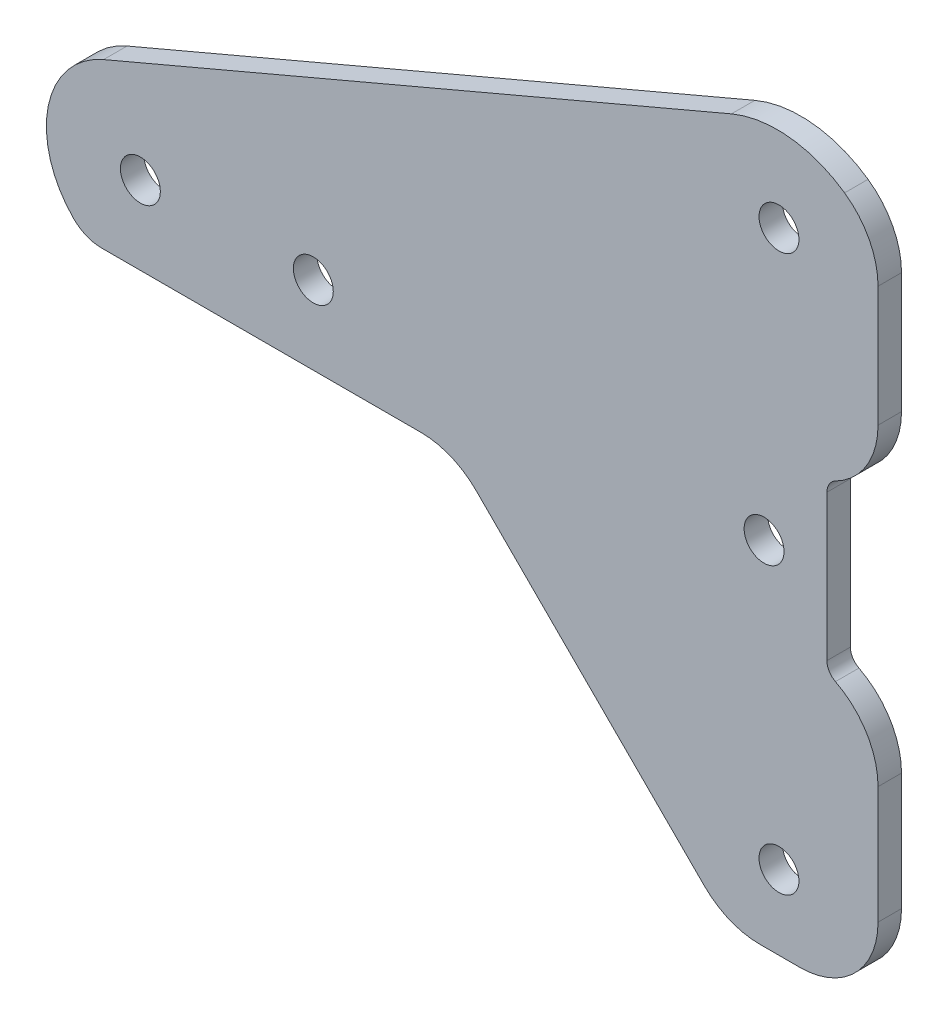
SolidWorks part; units mm, degrees
material "AISI 1020"
ref_plane "Front Plane" through (0, 0, 0) normal (0, 0, 1) x (1, 0, 0)
ref_plane "Top Plane" through (0, 0, 0) normal (0, 1, 0) x (1, 0, 0)
ref_plane "Right Plane" through (0, 0, 0) normal (1, 0, 0) x (0, 0, -1)
sketch "Sketch1" plane through (0, 0, 0) normal (0, 0, 1) x (1, 0, 0)
  line L0 (0, 20.0008) -> (0, 35.3808)
  line L1 (0, -20.0008) -> (0, -35.0008)
  line L2 (-18.7332, 45.0875) -> (-98.965, 10.9816)
  line L3 (-99.252, -10.003) -> (-58.412, -10.003)
  line L4 (-51.3409, -12.932) -> (-22.2011, -42.0718)
  line L5 (-15.13, -45.0008) -> (-10, -45.0008)
  line L6 (-6.53, 9.32) -> (-6.53, -9.32)
  arc A0 (0, -35.0008) -> (-10, -45.0008) centre (-10, -35.0008) cw
  arc A1 (-15.13, -45.0008) -> (-22.2011, -42.0718) centre (-15.13, -35.0008) cw
  arc A2 (0, 20.0008) -> (-5.4417, 11.1001) centre (-10, 20.0008) cw
  arc A3 (-5.4417, 11.1001) -> (-6.53, 9.32) centre (-4.53, 9.32) ccw
  arc A4 (0, -20.0008) -> (-5.4417, -11.1001) centre (-10, -20.0008) ccw
  arc A5 (-5.4417, -11.1001) -> (-6.53, -9.32) centre (-4.53, -9.32) cw
  arc A6 (-58.412, -10.003) -> (-51.3409, -12.932) centre (-58.412, -20.003) cw
  arc A9 (-18.7332, 45.0875) -> (-4.27, 43.5763) centre (-12.865, 31.283) cw
  arc A10 (-4.27, 43.5763) -> (0, 35.3808) centre (-10, 35.3808) cw
  arc A11 (-98.965, 10.9816) -> (-102.8076, -8.5185) centre (-94.2657, -0.0731) ccw
  arc A12 (-102.8076, -8.5185) -> (-99.252, -10.003) centre (-99.252, -5.003) ccw
  circle A13 centre (-94.2643, -0.003) radius 2.55
  circle A14 centre (-72.1643, -0.003) radius 2.55
  circle A15 centre (-14.5643, -0.003) radius 2.55
  circle A16 centre (-12.66, 35.4992) radius 2.55
  circle A17 centre (-12.66, -35.5008) radius 2.55
  point P24 (-6.53, 0)
  point P33 (-106.0511, 2.2493)
  dimension "D3" = 10
  dimension "D5" = 10
  dimension "D9" = 10
  dimension "D10" = 10
  dimension "D12" = 2
  dimension "D13" = 2
  dimension "D14" = 10
  dimension "D16" = 10
  dimension "D15" = 6.53
  dimension "D18" = 4.27
  dimension "D19" = 15
  dimension "D21" = 5
  dimension "D22" = 12
  dimension "D23" = 10
  dimension "D24" = 5.1
  dimension "D25" = 22.1
  dimension "D26" = 5.1
  dimension "D27" = 10
  dimension "D28" = 5.1
  dimension "D29" = 5.1
  dimension "D30" = 5.1
  dimension "D31" = 57.6
  dimension "D32" = 12.66
  dimension "D33" = 9.5
  dimension "D34" = 71
  dimension "D1" = 15.38
  dimension "D2" = 15
  dimension "D4" = 5.13
  dimension "D6" = 41.21
  dimension "D7" = 135
  dimension "D8" = 23.03
  dimension "D11" = 18.64
  dimension "D17" = 87.18
  dimension "D20" = 40.84
extrude "Boss-Extrude2" add sketch "Sketch1" along normal blind 3
